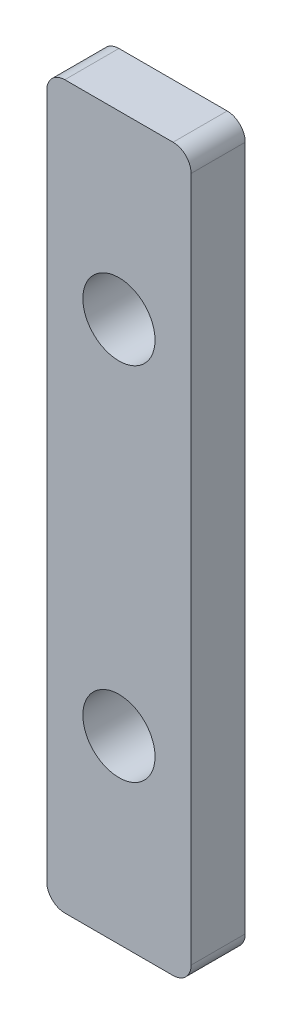
SolidWorks part; units mm, degrees
ref_plane "Front Plane" through (0, 0, 0) normal (0, 0, 1) x (1, 0, 0)
ref_plane "Top Plane" through (0, 0, 0) normal (0, 1, 0) x (1, 0, 0)
ref_plane "Right Plane" through (0, 0, 0) normal (1, 0, 0) x (0, 0, -1)
sketch "Sketch1" plane through (0, 0, 0) normal (0, 0, 1) x (1, 0, 0)
  line L0 (4, 40) -> (4, 0) construction
  line L1 (0, 0) -> (8, 0)
  line L2 (0, 0) -> (0, 40)
  line L3 (0, 40) -> (8, 40)
  line L4 (8, 0) -> (8, 40)
  circle A0 centre (4, 10) radius 2
  circle A1 centre (4, 30) radius 2
  dimension "D2" = 4
  dimension "D1" = 20
  dimension "D3" = 10
  dimension "D4" = 10
  dimension "D5" = 4
  dimension "D6" = 4
extrude "Boss-Extrude1" add sketch "Sketch1" along normal blind 3
fillet "Fillet1" radius 1 4 edges at (8, 0, 1.5) (0, 0, 1.5) (0, 40, 1.5) (8, 40, 1.5)
